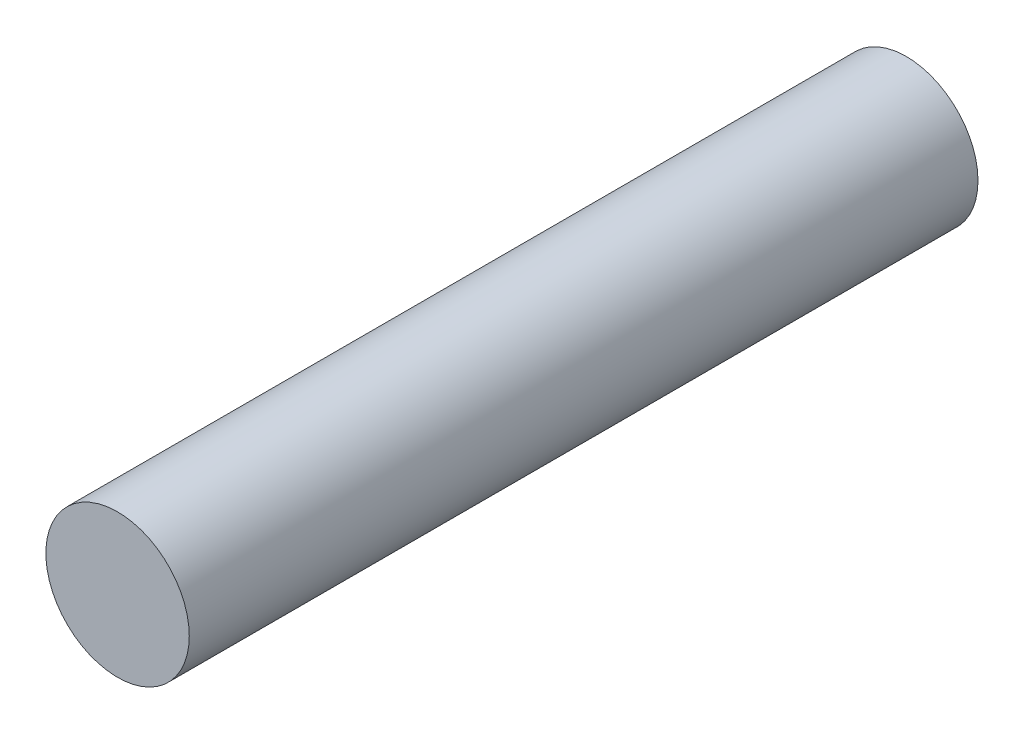
SolidWorks part; units mm, degrees
ref_plane "Спереди" through (0, 0, 0) normal (0, 0, 1) x (1, 0, 0)
ref_plane "Сверху" through (0, 0, 0) normal (0, 1, 0) x (1, 0, 0)
ref_plane "Справа" through (0, 0, 0) normal (1, 0, 0) x (0, 0, -1)
sketch "Эскиз1" plane through (0, 0, 0) normal (0, 0, 1) x (1, 0, 0)
  circle A0 centre (0, 0) radius 2
  dimension "D1" = 4
extrude "Шпилька на тяги" add sketch "Эскиз1" along normal blind 22
